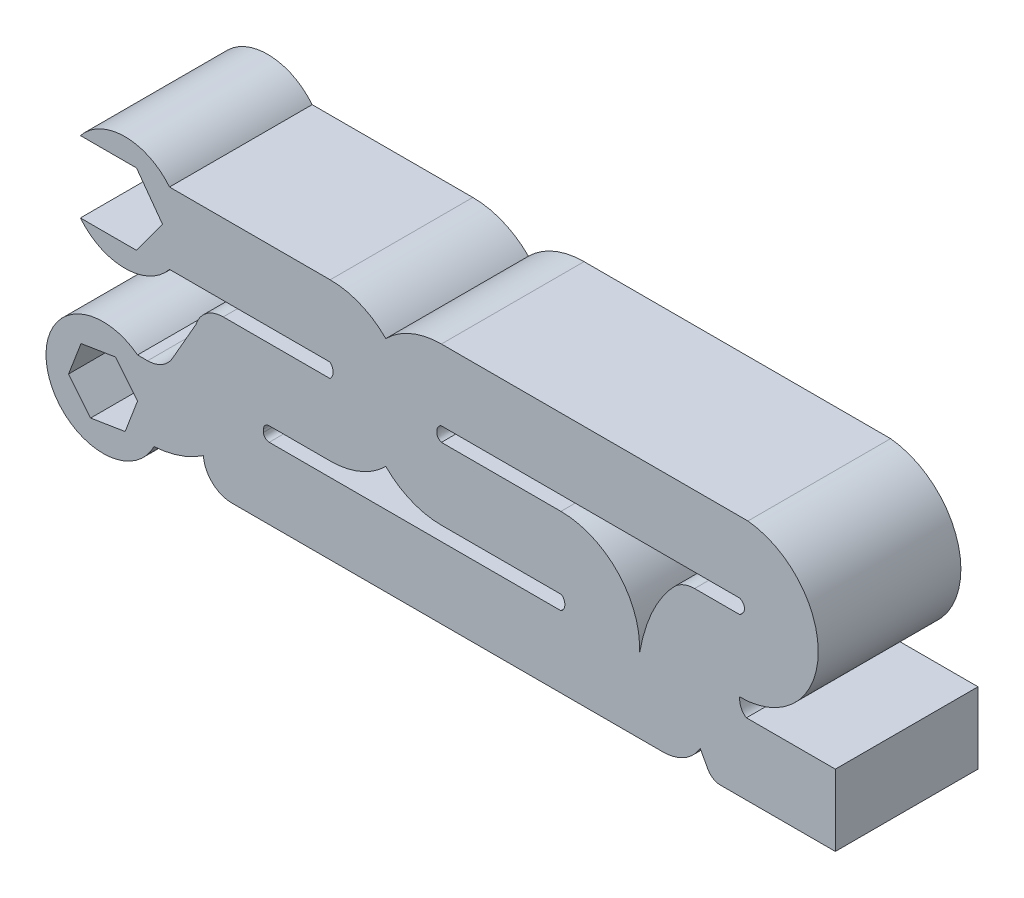
SolidWorks part; units mm, degrees
ref_plane "Front Plane" through (0, 0, 0) normal (0, 0, 1) x (1, 0, 0)
ref_plane "Top Plane" through (0, 0, 0) normal (0, 1, 0) x (1, 0, 0)
ref_plane "Right Plane" through (0, 0, 0) normal (1, 0, 0) x (0, 0, -1)
sketch "Sketch1" plane through (0, 0, 0) normal (0, 0, 1) x (1, 0, 0)
  line L0 (-5.2653, 3.6425) -> (-8.0727, 3.6425) construction
  line L7 (-8.0727, 3.6425) -> (-5.2653, 3.6425) construction
  line L8 (-5.2653, 3.6425) -> (11.9273, 3.6425) construction
  line L9 (-8.0727, 3.6425) -> (-8.0727, -6.3575) construction
  line L10 (-4.8591, 2.8925) -> (-6.8265, 2.8925)
  line L16 (-3.951, 1.6425) -> (-4.8591, 2.8925)
  line L17 (-3.951, 1.6425) -> (-1.913, 1.6425) construction
  line L21 (-4.8591, 0.3925) -> (-3.951, 1.6425)
  line L22 (-4.8591, 0.3925) -> (-6.8265, 0.3925)
  line L23 (-4.8591, 2.8925) -> (-5.8428, 2.8925)
  line L24 (-4.8591, 0.3925) -> (-6.8265, 0.3925)
  line L26 (-6.3286, 1.6425) -> (-6.3286, 0.8699) [skipped]
  line L27 (-5.5939, 0.6312) -> (-4.8591, 0.3925) [skipped]
  line L28 (-4.8591, 2.8925) -> (-5.5939, 2.6537) [skipped]
  arc A2 (-6.8265, 0.3925) -> (-6.8265, 2.8925) centre (-5.2653, 1.6425) ccw
  dimension "D2" = 4
  dimension "D1" = 20
  dimension "D4" = 2.5
extrude "Boss-Extrude1" add sketch "Sketch1" along normal blind 5 contours L22 A2 L10 L16 L21
sketch "Sketch2" plane through (0, 0, 0) normal (0, 0, -1) x (-1, 0, 0)
  line L0 (4.8591, 2.8925) -> (-1.9273, 2.8925)
  line L1 (4.8591, 0.3925) -> (-1.9273, 0.3925)
  line L2 (2.9977, 0.3925) -> (2.9977, -2.7272) construction
  line L3 (2.9977, -0.6075) -> (-3.3377, -0.6075)
  line L4 (-1.9273, 0.3925) -> (-1.9273, 2.8925)
  arc A0 (-1.9273, 2.8925) -> (0.7185, -0.6075) centre (-1.9273, 0.1425) ccw
  arc M10 (6.8265, 2.8925) -> (6.8265, 0.3925) centre (5.2653, 1.6425) ccw
  dimension "D2" = 5.5
  dimension "D1" = 10
  dimension "D3" = 1
extrude "Boss-Extrude2" add sketch "Sketch2" against normal blind 5 contours L4 L1 L0 M10
sketch "Sketch3" plane through (0, 0, 5) normal (0, 0, 1) x (1, 0, 0)
  line L0 (1.9273, -0.6075) -> (-1.6944, -0.6075)
  line L1 (-2.9977, -0.6075) -> (3.3377, -0.6075) construction
  line L2 (-2.6604, -1.8664) -> (-1.6433, -5.6619)
  line L3 (-1.4448, -6.4031) -> (6.5552, -6.4031) construction
  line L4 (-2.9977, 0.3925) -> (-2.9977, -2.7272) construction
  line L5 (-0.6774, -6.4031) -> (6.5552, -6.4031)
  line L6 (1.9273, -3.1075) -> (0.521, -3.1075)
  line L7 (0.3279, -3.3593) -> (0.4338, -3.7549)
  line L8 (0.627, -3.9031) -> (6.5552, -3.9031)
  line L9 (-2.9977, -0.6075) -> (-1.4448, -6.4031) construction
  line L10 (1.9273, -0.6075) -> (-2.9977, -0.6075) construction
  line L11 (0.4736, -3.9031) -> (6.5552, -3.9031) construction
  line L12 (0.2604, -3.1075) -> (0.4736, -3.9031) construction
  line L13 (1.9273, -3.1075) -> (0.2604, -3.1075) construction
  line L14 (0.521, -3.1075) -> (-1.6944, -0.6075)
  line L15 (6.5552, -3.9031) -> (6.5552, -6.4031)
  arc A0 (-0.6774, -6.4031) -> (-1.6433, -5.6619) centre (-0.6774, -5.4031) cw
  arc A1 (-1.6944, -0.6075) -> (-2.6604, -1.8664) centre (-1.6944, -1.6075) ccw
  arc A2 (0.627, -3.9031) -> (0.4338, -3.7549) centre (0.627, -3.7031) cw
  arc A3 (0.3279, -3.3593) -> (0.521, -3.1075) centre (0.521, -3.3075) cw
  point P16 (-1.4448, -6.4031)
  dimension "D5" = 1
  dimension "D2" = 0.2
  dimension "D1" = 15
  dimension "D3" = 8
  dimension "D4" = 2.5
sketch "Sketch7" plane through (0, 0, 0) normal (0, 0, -1) x (-1, 0, 0)
  line L2 (1.5168, -5.6075) -> (-5.5661, -5.6075)
  line L3 (2.8163, -1.1939) -> (2.5131, -4.6939)
  line L4 (0.4104, -3.1075) -> (-5.5661, -3.1075) construction
  line L5 (-1.9273, -2.6075) -> (0.2104, -2.6075)
  line L6 (0.4104, -2.8075) -> (0.4104, -2.9075)
  line L7 (6.8265, 0.3925) -> (4.8591, 0.3925)
  line L8 (4.8591, 0.3925) -> (3.951, 1.6425)
  line L9 (3.951, 1.6425) -> (4.8591, 2.8925)
  line L10 (4.8591, 2.8925) -> (6.8265, 2.8925)
  line L11 (3.704, 2.8925) -> (-1.9273, 2.8925)
  line L12 (-1.9273, 2.8925) -> (-1.9273, 0.3925)
  line L13 (-1.9273, 0.3925) -> (3.704, 0.3925)
  line L14 (6.8265, 0.3925) -> (4.8591, 0.3925)
  line L15 (4.8591, 0.3925) -> (3.951, 1.6425)
  line L16 (3.951, 1.6425) -> (4.8591, 2.8925)
  line L17 (4.8591, 2.8925) -> (6.8265, 2.8925)
  line L18 (3.704, 2.8925) -> (-1.9273, 2.8925)
  line L19 (-1.9273, 2.8925) -> (-1.9273, 0.3925)
  line L20 (-1.9273, 0.3925) -> (3.704, 0.3925)
  line L21 (-1.9273, -2.6075) -> (-1.9273, -0.1075)
  line L22 (-1.9273, -0.1075) -> (1.82, -0.1075)
  line L23 (-5.5661, -3.1075) -> (-5.5661, -5.6075)
  line L24 (2.8191, -1.1517) -> (2.5014, -4.7824) construction
  line L25 (0.2104, -3.1075) -> (-5.5661, -3.1075)
  line L26 (0.4104, -2.6075) -> (0.4104, -3.1075) construction
  line L27 (-1.9273, -2.6075) -> (0.4104, -2.6075) construction
  line L28 (2.9104, -5.6075) -> (-5.5661, -5.6075) construction
  line L29 (-1.9273, -0.1075) -> (2.9104, -0.1075) construction
  line L30 (2.9104, -0.1075) -> (2.9104, -5.6075) construction
  arc A1 (0.2104, -3.1075) -> (0.4104, -2.9075) centre (0.2104, -2.9075) ccw
  arc A2 (6.8265, 2.8925) -> (3.704, 2.8925) centre (5.2653, 1.6425) ccw
  arc A3 (3.704, 0.3925) -> (6.8265, 0.3925) centre (5.2653, 1.6425) ccw
  arc A4 (6.8265, 2.8925) -> (3.704, 2.8925) centre (5.2653, 1.6425) ccw
  arc A5 (3.704, 0.3925) -> (6.8265, 0.3925) centre (5.2653, 1.6425) ccw
  arc A10 (-1.9273, 2.8925) -> (0.8113, -0.1075) centre (-1.9273, 0.1425) ccw
  arc A11 (0.2104, -2.6075) -> (0.4104, -2.8075) centre (0.2104, -2.8075) cw
  arc A12 (1.5168, -5.6075) -> (2.5131, -4.6939) centre (1.5168, -4.6075) ccw
  arc A13 (2.8163, -1.1939) -> (1.82, -0.1075) centre (1.82, -1.1075) ccw
  arc A14 (-2.8275, -3.1075) -> (-2.8465, -2.4494) centre (-5.5661, -2.8575) ccw
  arc A15 (-4.6468, -0.2657) -> (-5.5661, -5.6075) centre (-5.5661, -2.8575) ccw
  spline S0 degree 3 poles (-1.9273, 0.3925) (-2.0271, 0.2877) (-2.096, 0.0761) (-1.9273, -0.1075) knots 0 0 0 0 1 1 1 1
  line M18 (-1.9273, 2.8925) -> (-1.9273, 0.3925)
  dimension "D2" = 5.5
  dimension "D7" = 0.2
  dimension "D5" = 1
  dimension "D4" = 5.5
  dimension "D3" = 2.5
  dimension "D1" = 0
  dimension "D8" = 2.5
extrude "Boss-Extrude4" add sketch "Sketch7" against normal blind 5 contours S0 A10 L21 M18 | L21 A10 L22 | L3 A13 L22 A10 L5 A11 L6 A1 L25 L23 L2 A12
sketch "Sketch8" plane through (0, 0, 0) normal (0, 0, -1) x (-1, 0, 0)
  line L0 (-1.9273, 2.8925) -> (-11.917, 2.8925) construction
  line L1 (-5.8251, -2.6075) -> (-10.014, -2.6075)
  line L2 (-5.5661, -5.6075) -> (-10.014, -5.6075) construction
  line L3 (-5.5661, -5.6075) -> (-10.014, -5.6075)
  line L4 (-5.5661, -3.1075) -> (-10.014, -3.1075)
  line L5 (-10.014, -0.0927) -> (-5.8251, -0.0927)
  line L6 (-5.8251, 0.4073) -> (-8.5637, 0.4073)
  line L7 (-5.5661, -5.6075) -> (-5.5661, -3.1075)
  line L8 (-5.8251, 2.8925) -> (-16.5682, 2.8925)
  line L9 (-8.5637, 0.4073) -> (-16.2824, 0.4073)
  line L10 (-14.6987, -0.0927) -> (-16.2824, -0.0927)
  line L12 (-15.607, -5.6071) -> (-16.213, -5.6071)
  line L13 (-14.6987, -0.0927) -> (-16.2824, -0.0927)
  line L14 (-16.213, -5.6071) -> (-19.6318, -5.6071)
  line L15 (-16.5158, -3.1075) -> (-19.6318, -3.1075)
  line L20 (-10.014, -5.6075) -> (-13.587, -5.6075)
  line L21 (-10.014, -5.6075) -> (-12.514, -5.6075)
  line L22 (-14.894, -4.8435) -> (-15.1679, -5.3463)
  line L24 (-19.6318, -3.1075) -> (-19.6318, -5.6071)
  arc A0 (-5.8251, -2.6075) -> (-5.8251, 2.8925) centre (-5.8251, 0.1425) ccw
  arc A2 (-10.014, -0.0927) -> (-10.014, -5.6075) centre (-10.014, -2.8501) ccw
  arc A5 (-13.9734, -0.4041) -> (-14.6987, -0.0927) centre (-14.6987, -1.0927) ccw
  arc A6 (-13.587, -5.6075) -> (-14.894, -4.8435) centre (-13.587, -4.1075) cw
  arc A7 (-16.5682, 2.8925) -> (-16.2824, -2.5927) centre (-16.2824, 0.1573) ccw
  arc A8 (-15.607, -5.6071) -> (-15.1679, -5.3463) centre (-15.607, -5.1071) ccw
  spline S0 degree 3 poles (-10.014, -3.1075) (-10.2191, -2.9937) (-10.1736, -2.6554) (-10.014, -2.6075) knots 0 0 0 0 1 1 1 1
  spline S1 degree 3 poles (-5.8251, 0.4073) (-5.6611, 0.3778) (-5.5622, 0.005) (-5.8251, -0.0927) knots 0 0 0 0 1 1 1 1
  spline S2 degree 3 poles (-16.2824, 0.4073) (-16.5036, 0.3143) (-16.5008, 0.0483) (-16.2824, -0.0927) knots 0 0 0 0 1 1 1 1
  spline S3 degree 3 poles (-12.7526, -3.1075) (-12.9585, -1.8947) (-13.3907, -1.018) (-13.9734, -0.4041) knots 0 0 0 0 0.535473 0.535473 0.535473 0.535473
  spline S4 degree 3 poles (-16.5158, -3.1075) (-16.3075, -3.0014) (-16.2587, -2.6908) (-16.2824, -2.5927) knots 0 0 0 0 1 1 1 1
  point P28 (-16.2824, 0.1573)
  dimension "D1" = 5.5
  dimension "D2" = 0.5
  dimension "D3" = 0.5
  dimension "D4" = 1
  dimension "D8" = 1.5
  dimension "D5" = 2.3757
  dimension "D9" = 3.573
  dimension "D10" = 2.5
extrude "Boss-Extrude6" add sketch "Sketch8" against normal blind 5
sketch "Sketch9" plane through (0, 0, 0) normal (0, 0, -1) x (-1, 0, 0)
  line L0 (8.0727, -6.3575) -> (0.3249, -6.3575) construction
  line L1 (4.8239, -2.7642) -> (4.4722, -2.7642)
  line L2 (5.5968, -3.2133) -> (4.8239, -4.1629)
  line L3 (4.8239, -4.1629) -> (5.2598, -5.3072)
  line L4 (5.2598, -5.3072) -> (6.4686, -5.5018)
  line L5 (6.4686, -5.5018) -> (7.2416, -4.5522)
  line L6 (7.2416, -4.5522) -> (6.8057, -3.4079)
  line L7 (6.8057, -3.4079) -> (5.5968, -3.2133)
  line L8 (3.6044, -2.2611) -> (2.776, -0.8142)
  line L11 (3.6044, -2.2611) -> (2.557, -0.4316) construction
  line L12 (2.8163, -1.1939) -> (2.5131, -4.6939) construction
  line L13 (2.8163, -1.1939) -> (2.5131, -4.6939)
  line L14 (1.4348, -3.5032) -> (0.3874, -1.6737) construction
  line L15 (4.8239, -5.2642) -> (4.4722, -5.2642) construction
  circle A1 centre (6.0327, -4.3575) radius 2
  circle A2 centre (6.0327, -4.3575) radius 1.0604 construction
  arc A4 (2.8163, -1.1939) -> (1.82, -0.1075) centre (1.82, -1.1075) ccw construction
  arc A5 (3.6044, -2.2611) -> (4.4722, -2.7642) centre (4.4722, -1.7642) ccw
  arc A6 (2.5155, -4.6662) -> (4.2464, -5.257) centre (4.4722, -1.7642) ccw
  arc A7 (2.8163, -1.1939) -> (2.776, -0.8142) centre (1.82, -1.1075) ccw
  arc A8 (1.4348, -3.5032) -> (4.4722, -5.2642) centre (4.4722, -1.7642) ccw construction
  arc M7 (2.8163, -1.1939) -> (1.82, -0.1075) centre (1.82, -1.1075) ccw
  dimension "D2" = 4
  dimension "D1" = 1
  dimension "D3" = 2.5
  dimension "D4" = 2.4489
extrude "Boss-Extrude7" add sketch "Sketch9" against normal blind 5 contours L13 A6 A1 L1 A5 L8 M7 | A1 L7 L6 L5 L4 L3 L2
